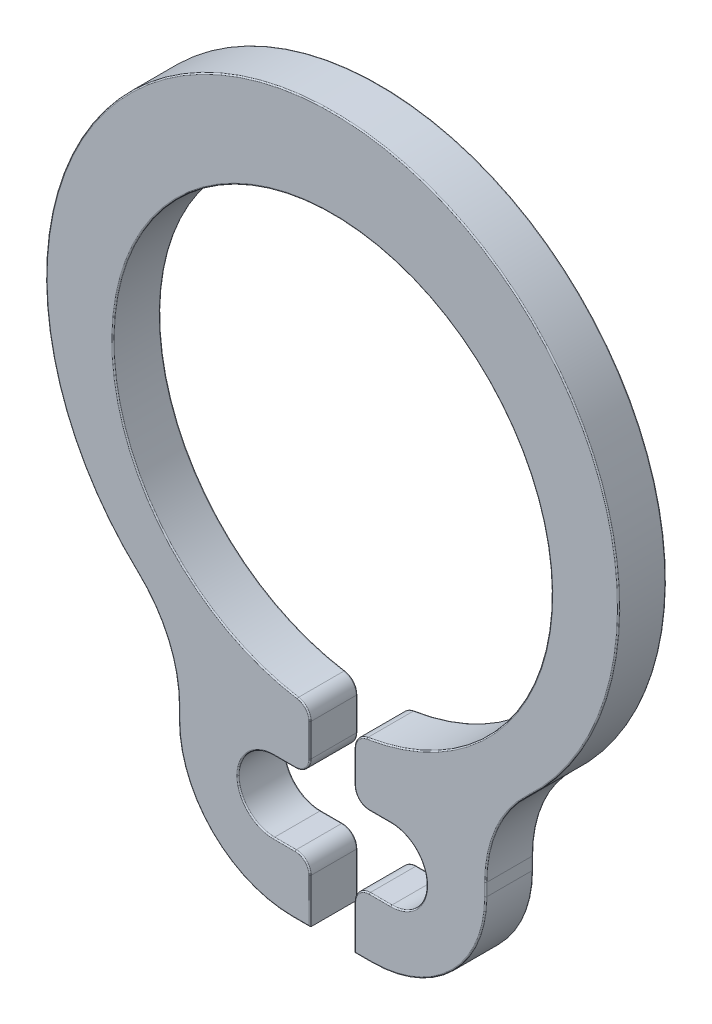
SolidWorks part; units mm, degrees
ref_plane "Front Plane" through (0, 0, 0) normal (0, 0, 1) x (1, 0, 0)
ref_plane "Top Plane" through (0, 0, 0) normal (0, 1, 0) x (1, 0, 0)
ref_plane "Right Plane" through (0, 0, 0) normal (1, 0, 0) x (0, 0, -1)
sketch "Sketch1" plane through (0, 0, 0) normal (0, 0, 1) x (1, 0, 0)
  line L0 (0, 6.05) -> (0, -6.05) construction
  line L1 (-0.99, -4.45) -> (0.99, -4.45) construction
  line L2 (-0.99, -3.85) -> (0.99, -3.85)
  line L3 (-0.99, -5.05) -> (0.99, -5.05)
  line L4 (1.59, -4.45) -> (2.59, -4.45) construction
  line L5 (0, -2.85) -> (0, -3.85) construction
  circle A0 centre (0, 0.85) radius 3.7
  arc A3 (-0.99, -3.85) -> (-0.99, -5.05) centre (-0.99, -4.45) ccw
  arc A4 (0.99, -5.05) -> (0.99, -3.85) centre (0.99, -4.45) ccw
  circle A5 centre (0, 1.22) radius 4.83 construction
  circle A6 centre (0, 0.85) radius 4 construction
  circle A7 centre (0, 0.85) radius 3.8 construction
  point P6 (0, 4.55)
  point P7 (0, -2.85)
  point P10 (0, -4.45)
  dimension "For OD" = 8
  dimension "ID" = 7.4
  dimension "Band Width" = 1.5
  dimension "Tap Height" = 3.2
  dimension "Tap ID" = 1.2
  dimension "D3" = 1.6
  dimension "Tap Width Ref" = 5.18
  dimension "D1" = 0.37
sketch "Sketch2" plane through (0, 0, 0) normal (1, 0, 0) x (0, 0, -1)
  line L0 (-0.4, 6.05) -> (0.4, 6.05) construction
  line L1 (0, 7.75) -> (0, -6.05) construction
  line L2 (0, 6.05) -> (0, -6.05) construction
  line L3 (-0.45, 7.75) -> (0.45, 7.75) construction
  line L4 (-0.45, -6.05) -> (0.45, -6.05) construction
  dimension "Thickness" = 0.8
  dimension "For Groove Width" = 0.9
sketch "Sketch3" plane through (0, 0, 0) normal (0, 0, 1) x (1, 0, 0)
  line L0 (-0.99, -5.05) -> (0.99, -5.05) construction
  line L1 (-0.99, -3.85) -> (0.99, -3.85) construction
  line L2 (-0.99, -5.05) -> (0.99, -5.05)
  line L3 (-0.99, -3.85) -> (0.99, -3.85)
  line L4 (2.59, -3.9186) -> (2.59, -4.13)
  line L5 (-0.67, -6.05) -> (0.67, -6.05)
  line L6 (-2.59, -3.9186) -> (-2.59, -4.13)
  line L7 (-1.59, -4.45) -> (-2.59, -4.45) construction
  line L8 (1.59, -4.45) -> (2.59, -4.45) construction
  arc A0 (-0.99, -3.85) -> (-0.99, -5.05) centre (-0.99, -4.45) ccw construction
  arc A1 (0.99, -5.05) -> (0.99, -3.85) centre (0.99, -4.45) ccw construction
  arc A2 (-0.99, -3.85) -> (-0.99, -5.05) centre (-0.99, -4.45) ccw
  arc A3 (0.99, -5.05) -> (0.99, -3.85) centre (0.99, -4.45) ccw
  circle A4 centre (0, 0.85) radius 3.7 construction
  circle A5 centre (0, 0.85) radius 3.7
  arc A6 (-3.2875, -2.3186) -> (3.2875, -2.3186) centre (0, 1.22) cw
  arc A8 (3.2875, -2.3186) -> (2.59, -3.9186) centre (4.7739, -3.9186) ccw
  arc A9 (2.59, -4.13) -> (0.67, -6.05) centre (0.67, -4.13) cw
  arc A10 (-3.2875, -2.3186) -> (-2.59, -3.9186) centre (-4.7739, -3.9186) cw
  arc A11 (-2.59, -4.13) -> (-0.67, -6.05) centre (-0.67, -4.13) ccw
  circle A12 centre (0, 1.22) radius 4.83 construction
  dimension "D1" = 1.6
  dimension "D2" = 1.92
  dimension "D3" = 1
extrude "Boss-Extrude1" add sketch "Sketch3" along normal mid plane 0.8
sketch "Sketch4" plane through (0, 0, 0) normal (0, 0, 1) x (1, 0, 0)
  line L0 (0, 0.85) -> (0, -6.05)
extrude "Cut-Extrude-Thin1" cut sketch "Sketch4" against normal through all both and the other way through all thin thin type mid plane wall 0.75
fillet "Fillet2" radius 0.25 6 edges at (0.375, -5.05, 0) (-0.375, -5.05, 0) (0.375, -3.85, 0) (0.375, -2.8309, 0) (-0.375, -3.85, 0) (-0.375, -2.8309, 0)
fillet "Fillet1" radius 0.02 52 edges at (-0.8075, -5.05, -0.4) (-1.59, -4.45, -0.4) (-0.8075, -3.85, -0.4) (0, 4.55, -0.4) (0.8075, -3.85, -0.4) (1.59, -4.45, -0.4) (0.8075, -5.05, -0.4) (0.375, -5.675, -0.4) (0.5225, -6.05, -0.4) (2.0276, -5.4876, -0.4) (2.59, -4.0243, -0.4) (2.7719, -3.0459, -0.4) (0, 6.05, -0.4) (-2.7719, -3.0459, -0.4) (-2.59, -4.0243, -0.4) (-2.0276, -5.4876, -0.4) (-0.5225, -6.05, -0.4) (-0.375, -5.675, -0.4) (-2.0276, -5.4876, 0.4) (-2.59, -4.0243, 0.4) (-2.7719, -3.0459, 0.4) (0, 6.05, 0.4) (2.7719, -3.0459, 0.4) (2.59, -4.0243, 0.4) (2.0276, -5.4876, 0.4) (0.5225, -6.05, 0.4) (0.375, -5.675, 0.4) (0.8075, -5.05, 0.4) (1.59, -4.45, 0.4) (0.8075, -3.85, 0.4) (0, 4.55, 0.4) (-0.8075, -3.85, 0.4) (-1.59, -4.45, 0.4) (-0.8075, -5.05, 0.4) (-0.375, -5.675, 0.4) (-0.5225, -6.05, 0.4) (-0.4482, -5.1232, -0.4) (-0.4482, -3.7768, -0.4) (-0.375, -3.3251, -0.4) (-0.4348, -2.8881, -0.4) (0.4348, -2.8881, -0.4) (0.375, -3.3251, -0.4) (0.4482, -3.7768, -0.4) (0.4482, -5.1232, -0.4) (0.4482, -3.7768, 0.4) (0.375, -3.3251, 0.4) (0.4348, -2.8881, 0.4) (-0.4348, -2.8881, 0.4) (-0.375, -3.3251, 0.4) (-0.4482, -3.7768, 0.4) (-0.4482, -5.1232, 0.4) (0.4482, -5.1232, 0.4)
equation "\"D3@Sketch1\"=\"Tap Height@Sketch1\"*0.5"
equation "\"D1@Sketch3\"=\"Tap Height@Sketch1\"*0.5"
equation "\"D2@Sketch3\"=\"Tap Height@Sketch1\"*0.6"
equation "\"D1@Boss-Extrude1\" = \"Thickness@Sketch2\""
equation "\"D1@Sketch1\"= \"ID@Sketch1\" * 0.05"
equation "\"D1@Fillet2\"=\"D3@Sketch3\"*0.25"
